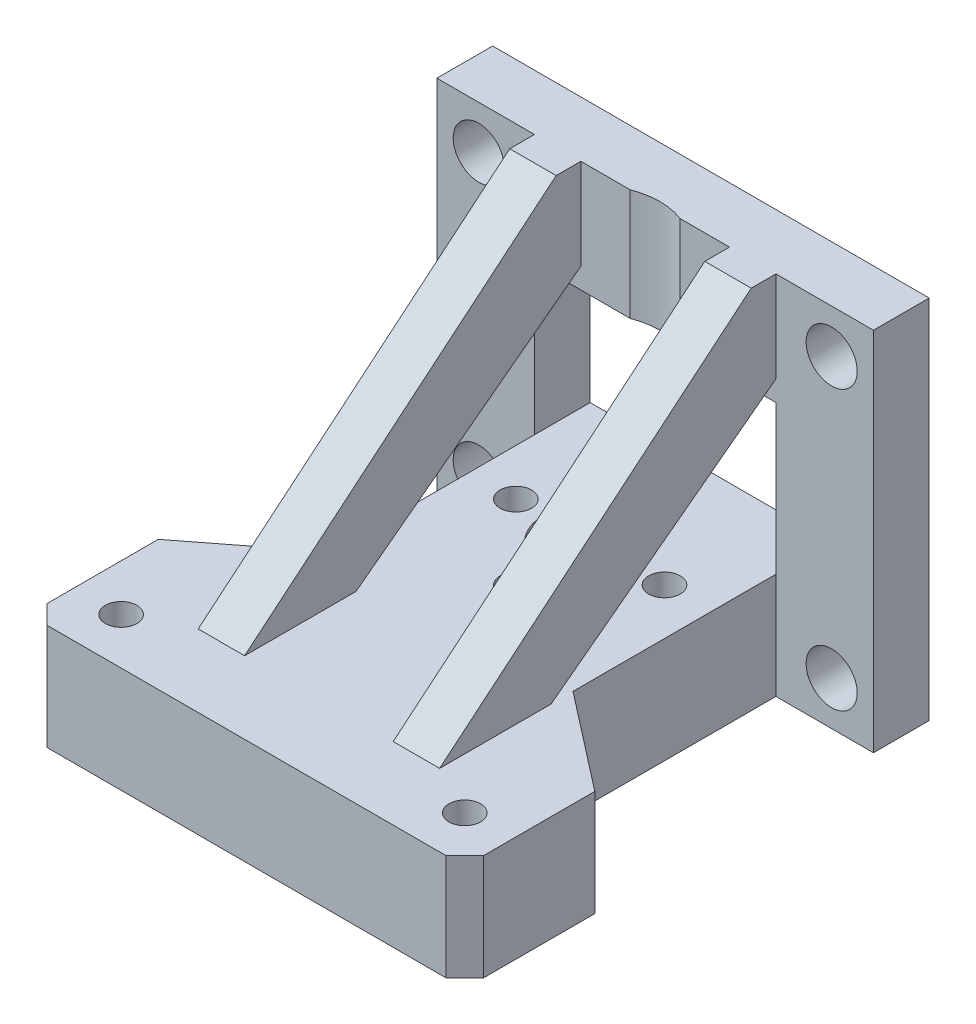
SolidWorks part; units mm, degrees
ref_plane "Front Plane" through (0, 0, 0) normal (0, 0, 1) x (1, 0, 0)
ref_plane "Top Plane" through (0, 0, 0) normal (0, 1, 0) x (1, 0, 0)
ref_plane "Right Plane" through (0, 0, 0) normal (1, 0, 0) x (0, 0, -1)
sketch "Sketch1" plane through (0, 0, 0) normal (0, 0, 1) x (1, 0, 0)
  line L1 (-23.5, -19.7) -> (23.5, -19.7)
  line L2 (-23.5, -19.7) -> (-23.5, 19.7)
  line L3 (-23.5, 19.7) -> (23.5, 19.7)
  line L4 (23.5, -19.7) -> (23.5, 19.7)
  line L5 (-23.5, -19.7) -> (23.5, 19.7) construction
  line L6 (-23.5, 19.7) -> (23.5, -19.7) construction
  point P0 (0, 0)
extrude "Boss-Extrude1" add sketch "Sketch1" along normal blind 50
sketch "Sketch2" plane through (0, 0, 0) normal (0, 0, -1) x (-1, 0, 0)
  line L0 (-23.5, 19.7) -> (23.5, 19.7) construction
  point P0 (19, 15)
  point P1 (-19, 15)
  point P2 (-19, -15)
  point P3 (19, -15)
sketch "Sketch3" plane through (0, 19.7, 0) normal (0, 1, 0) x (1, 0, 0)
  line L0 (0, 0) -> (0, -50) construction
  line L1 (23.5, -50) -> (23.5, 0) construction
  line L2 (23.5, -6) -> (13, -6)
  line L3 (13, -6) -> (13, -36)
  line L4 (13, -36) -> (23.5, -36)
  line L5 (23.5, -36) -> (23.5, -6)
  line L6 (23.5, 0) -> (-23.5, 0) construction
  line L7 (23.5, -50) -> (-23.5, -50) construction
  line L8 (-23.5, -36) -> (-23.5, -6)
  line L9 (-13, -36) -> (-23.5, -36)
  line L10 (-13, -6) -> (-13, -36)
  line L11 (-23.5, -6) -> (-13, -6)
extrude "Cut-Extrude1" cut sketch "Sketch3" against normal blind 50
sketch "Sketch19" plane through (0, -19.7, 0) normal (0, -1, 0) x (1, 0, 0)
  circle A0 centre (0, 13) radius 5
extrude "Cut-Extrude6" cut sketch "Sketch19" against normal through all
hole_wizard "M5 Clearance Hole1" positions "Sketch23" profile "Sketch24" hole size "M5" standard "ISO"
sketch "Sketch23" plane through (0, 0, 0) normal (0, 0, -1) x (-1, 0, 0)
  point P0 (-19, -15)
  point P3 (-19, 15)
  point P6 (19, 15)
  point P9 (19, -15)
sketch "Sketch24" plane through (19, -15, 0) normal (1, 0, 0) x (0, 1, 0)
  line L0 (0, 0) -> (0, 6)
  line L1 (0, 6) -> (2.75, 6)
  line L2 (2.75, 6) -> (2.75, 0)
  line L5 (2.75, 0) -> (0, 0)
  line L11 (0, -6.35) -> (0, 107.95) construction
  dimension "Thru Hole Dia." = 5.5
  dimension "Thru Hole Depth" = 6
sketch "Sketch25" plane through (0, 19.7, 0) normal (0, 1, 0) x (1, 0, 0)
  circle A0 centre (0, -13) radius 7.5
extrude "Cut-Extrude7" cut sketch "Sketch25" against normal blind 28 contours A0
sketch "Sketch26" plane through (0, 19.7, 0) normal (0, 1, 0) x (1, 0, 0)
  line L0 (13, -6) -> (13, -36)
  line L1 (13, -36) -> (23.5, -36)
  line L2 (23.5, -50) -> (23.5, -36) construction
  line L3 (13, -36) -> (23.5, -36) construction
  line L4 (23.5, -36) -> (23.5, -50)
  line L5 (23.5, -50) -> (-23.5, -50)
  line L6 (-23.5, -50) -> (-23.5, -36)
  line L7 (-23.5, -36) -> (-13, -36)
  line L8 (-13, -36) -> (-13, -6)
  line L9 (-13, -6) -> (13, -6)
extrude "Cut-Extrude8" cut sketch "Sketch26" against normal blind 28
sketch "Sketch27" plane through (0, 0, 6) normal (0, 0, 1) x (1, 0, 0)
  line L0 (13, -8.3) -> (-13, -8.3)
  line L1 (13, -8.3) -> (13, 7.7)
  line L2 (-13, -8.3) -> (-13, 7.7)
  line L3 (13, 7.7) -> (-13, 7.7)
extrude "Cut-Extrude9" cut sketch "Sketch27" against normal blind 28
sketch "Sketch28" plane through (0, -19.7, 0) normal (0, -1, 0) x (1, 0, 0)
  line L0 (0, 13) -> (0, 21) construction
  line L1 (0, 21) -> (0, 13) construction
  line L2 (0, 13) -> (8, 13) construction
  line L3 (0, 13) -> (0, 5) construction
  line L4 (0, 5) -> (0, 13) construction
  line L5 (0, 13) -> (-8, 13) construction
  line L6 (-23.5, 50) -> (-23.5, 36) construction
  line L7 (23.5, 50) -> (23.5, 36) construction
  line L10 (-23.5, 50) -> (23.5, 50) construction
  circle A0 centre (0, 21) radius 1.7
  circle A1 centre (8, 13) radius 1.7
  circle A2 centre (0, 5) radius 1.7
  circle A3 centre (-8, 13) radius 1.7
  circle A4 centre (-18.5, 45) radius 1.7
  circle A5 centre (18.5, 45) radius 1.7
  point P19 (0, 0)
  point P21 (14.4885, 50)
  point P22 (19.7206, 50)
  dimension "D1" = 5
  dimension "D2" = 5
  dimension "D3" = 5
  dimension "D4" = 5
extrude "Cut-Extrude10" cut sketch "Sketch28" against normal up to next
sketch "Sketch29" plane through (13, 0, 0) normal (1, 0, 0) x (0, 0, -1)
  line L0 (-42.2057, -8.3) -> (-30.2057, -8.3)
  line L1 (-36, -8.3) -> (-6, -8.3) construction
  line L2 (-30.2057, -8.3) -> (-6, 9.9198)
  line L3 (-6, 9.9198) -> (-6, 19.7)
  line L4 (-8.6595, 19.7) -> (-42.2057, -8.3)
  line L5 (-6, 19.7) -> (-8.6595, 19.7)
extrude "Boss-Extrude2" add sketch "Sketch29" against normal blind 26
sketch "Sketch30" plane through (0, 19.7, 0) normal (0, 1, 0) x (1, 0, 0)
  line L0 (13, -6) -> (8, -6) construction
  line L1 (-13, -6) -> (-8, -6) construction
  line L2 (8, -6) -> (-8, -6)
  line L3 (8, -6) -> (8, -47.7367)
  line L4 (-8, -6) -> (-8, -47.7367)
  line L5 (8, -47.7367) -> (-8, -47.7367)
extrude "Cut-Extrude11" cut sketch "Sketch30" against normal blind 28
sketch "Sketch31" plane through (0, -19.7, 0) normal (0, -1, 0) x (1, 0, 0)
  line L0 (-23.5, 36) -> (-13, 36)
  line L1 (-13, 36) -> (-13, 27.8469)
  line L2 (-13, 36) -> (-13, 6) construction
  line L3 (-13, 27.8469) -> (-23.5, 36)
  line L4 (13, 36) -> (13, 27.8469)
  line L5 (13, 6) -> (13, 36) construction
  line L6 (13, 27.8469) -> (23.5, 36)
  line L7 (23.5, 36) -> (13, 36)
extrude "Boss-Extrude3" add sketch "Sketch31" against normal up to vertex
chamfer "Chamfer1" distance 2 angle 45 2 edges at (-23.5, -14, 50) (23.5, -14, 50)
